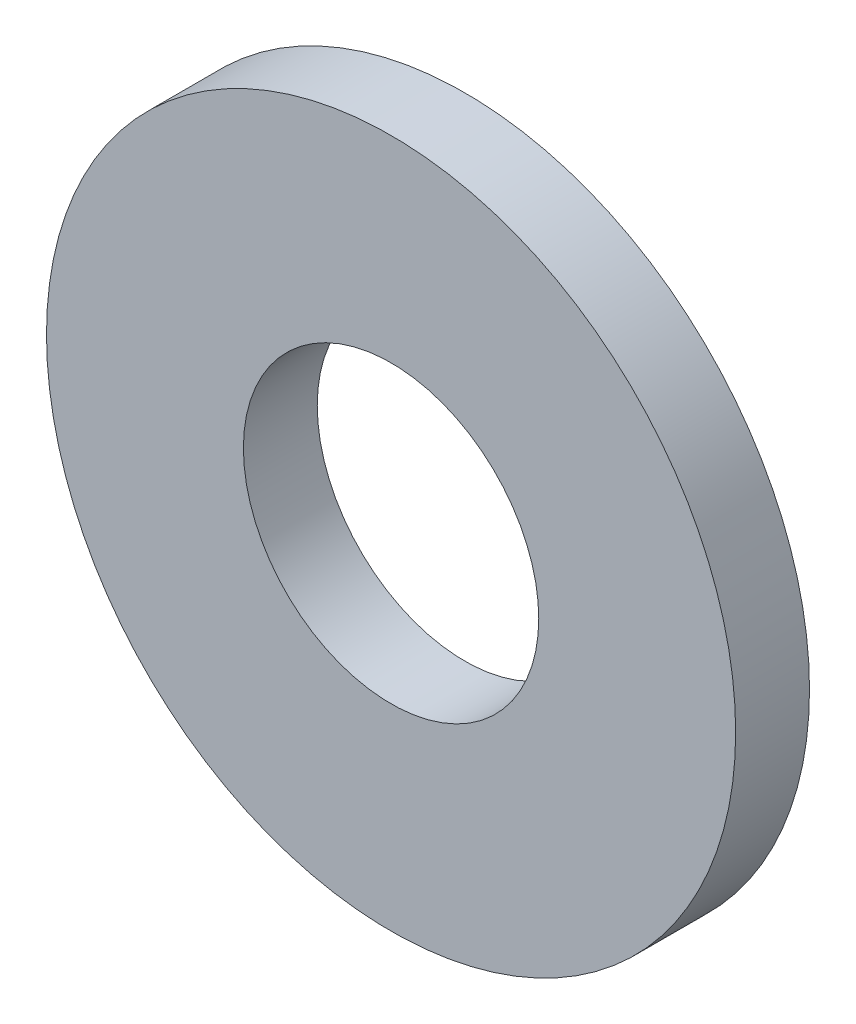
SolidWorks part; units mm, degrees
ref_plane "Front Plane" through (0, 0, 0) normal (0, 0, 1) x (1, 0, 0)
ref_plane "Top Plane" through (0, 0, 0) normal (0, 1, 0) x (1, 0, 0)
ref_plane "Right Plane" through (0, 0, 0) normal (1, 0, 0) x (0, 0, -1)
sketch "Sketch1" plane through (0, 0, 0) normal (0, 0, 1) x (1, 0, 0)
  circle A0 centre (0, 0) radius 3
  circle A1 centre (0, 0) radius 7
extrude "Extrude1" add sketch "Sketch1" along normal blind 1.5
